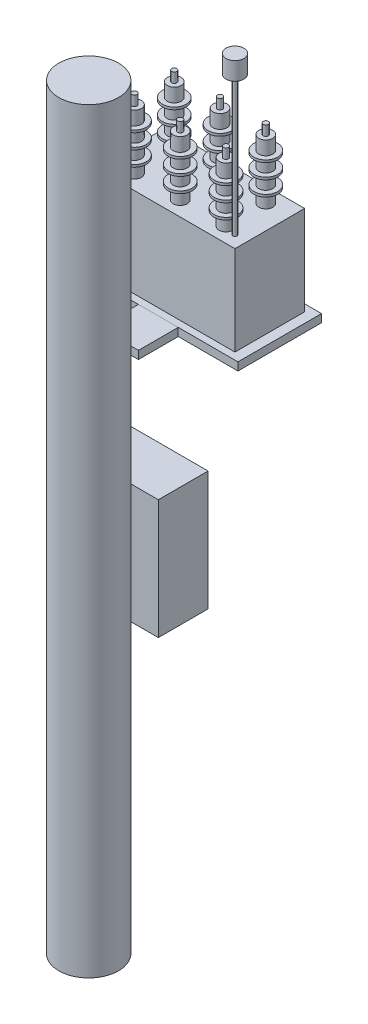
SolidWorks part; units mm, degrees
ref_plane "Front Plane" through (0, 0, 0) normal (0, 0, 1) x (1, 0, 0)
ref_plane "Top Plane" through (0, 0, 0) normal (0, 1, 0) x (1, 0, 0)
ref_plane "Right Plane" through (0, 0, 0) normal (1, 0, 0) x (0, 0, -1)
sketch "Sketch1" plane through (0, 0, 0) normal (0, 1, 0) x (1, 0, 0)
  line L1 (-350, -175) -> (350, -175)
  line L2 (-350, -175) -> (-350, 175)
  line L3 (-350, 175) -> (350, 175)
  line L4 (350, -175) -> (350, 175)
  line L5 (-350, -175) -> (350, 175) construction
  line L6 (-350, 175) -> (350, -175) construction
  point P0 (0, 0)
extrude "Tank" add sketch "Sketch1" along normal blind 450 separate body
sketch "Sketch2" plane through (0, 0, 0) normal (0, 1, 0) x (1, 0, 0)
  line L1 (-400, -210) -> (400, -210)
  line L2 (-400, -210) -> (-400, 210)
  line L3 (-400, 210) -> (400, 210)
  line L4 (400, -210) -> (400, 210)
  line L5 (-400, -210) -> (400, 210) construction
  line L6 (-400, 210) -> (400, -210) construction
  point P0 (0, 0)
extrude "Frame" add sketch "Sketch2" along normal blind 40 from offset 40 separate body
sketch "Sketch3" plane through (0, 0, 0) normal (0, 1, 0) x (1, 0, 0)
  line L0 (-400, -210) -> (400, -210) construction
  line L1 (-100, -410) -> (100, -410)
  line L2 (-100, -410) -> (-100, -210)
  line L3 (-100, -210) -> (100, -210)
  line L4 (100, -410) -> (100, -210)
  line L5 (-100, -410) -> (100, -210) construction
  line L6 (-100, -210) -> (100, -410) construction
  point P0 (0, -310)
extrude "Frame arm" add sketch "Sketch3" along normal blind 40 from offset 40 separate body
sketch "Sketch4" plane through (0, 0, 0) normal (0, 1, 0) x (1, 0, 0)
  line L1 (-200, -410) -> (200, -410)
  line L2 (-200, -410) -> (-200, -160)
  line L3 (-200, -160) -> (200, -160)
  line L4 (200, -410) -> (200, -160)
  line L5 (-200, -410) -> (200, -160) construction
  line L6 (-200, -160) -> (200, -410) construction
  point P0 (0, -285)
extrude "Control cabinet" add sketch "Sketch4" along normal blind 600 from offset 1200 separate body
sketch "Sketch5" plane through (0, 0, 0) normal (0, 1, 0) x (1, 0, 0)
  circle A0 centre (0, -560) radius 150
extrude "Pole" add sketch "Sketch5" along normal blind 3800 from offset 2600 separate body
sketch "Sketch6" plane through (0, 0, 0) normal (0, 1, 0) x (1, 0, 0)
  circle A0 centre (-230, 100) radius 35
extrude "Bushing Source A" add sketch "Sketch6" along normal blind 300 from offset 450 separate body
sketch "Sketch7" plane through (0, 0, 0) normal (0, 1, 0) x (1, 0, 0)
  circle A0 centre (-230, 100) radius 60
extrude "Shed Source A 1" add sketch "Sketch7" along normal blind 12 from offset 519 separate body
sketch "Sketch8" plane through (0, 0, 0) normal (0, 1, 0) x (1, 0, 0)
  circle A0 centre (-230, 100) radius 60
extrude "Shed Source A 2" add sketch "Sketch8" along normal blind 12 from offset 594 separate body
sketch "Sketch9" plane through (0, 0, 0) normal (0, 1, 0) x (1, 0, 0)
  circle A0 centre (-230, 100) radius 60
extrude "Shed Source A 3" add sketch "Sketch9" along normal blind 12 from offset 669 separate body
sketch "Sketch10" plane through (0, 0, 0) normal (0, 1, 0) x (1, 0, 0)
  circle A0 centre (-230, 100) radius 13
extrude "Terminal Source A" add sketch "Sketch10" along normal blind 50 from offset 750 separate body
sketch "Sketch11" plane through (0, 0, 0) normal (0, 1, 0) x (1, 0, 0)
  circle A0 centre (0, 100) radius 35
extrude "Bushing Source B" add sketch "Sketch11" along normal blind 300 from offset 450 separate body
sketch "Sketch12" plane through (0, 0, 0) normal (0, 1, 0) x (1, 0, 0)
  circle A0 centre (0, 100) radius 60
extrude "Shed Source B 1" add sketch "Sketch12" along normal blind 12 from offset 519 separate body
sketch "Sketch13" plane through (0, 0, 0) normal (0, 1, 0) x (1, 0, 0)
  circle A0 centre (0, 100) radius 60
extrude "Shed Source B 2" add sketch "Sketch13" along normal blind 12 from offset 594 separate body
sketch "Sketch14" plane through (0, 0, 0) normal (0, 1, 0) x (1, 0, 0)
  circle A0 centre (0, 100) radius 60
extrude "Shed Source B 3" add sketch "Sketch14" along normal blind 12 from offset 669 separate body
sketch "Sketch15" plane through (0, 0, 0) normal (0, 1, 0) x (1, 0, 0)
  circle A0 centre (0, 100) radius 13
extrude "Terminal Source B" add sketch "Sketch15" along normal blind 50 from offset 750 separate body
sketch "Sketch16" plane through (0, 0, 0) normal (0, 1, 0) x (1, 0, 0)
  circle A0 centre (230, 100) radius 35
extrude "Bushing Source C" add sketch "Sketch16" along normal blind 300 from offset 450 separate body
sketch "Sketch17" plane through (0, 0, 0) normal (0, 1, 0) x (1, 0, 0)
  circle A0 centre (230, 100) radius 60
extrude "Shed Source C 1" add sketch "Sketch17" along normal blind 12 from offset 519 separate body
sketch "Sketch18" plane through (0, 0, 0) normal (0, 1, 0) x (1, 0, 0)
  circle A0 centre (230, 100) radius 60
extrude "Shed Source C 2" add sketch "Sketch18" along normal blind 12 from offset 594 separate body
sketch "Sketch19" plane through (0, 0, 0) normal (0, 1, 0) x (1, 0, 0)
  circle A0 centre (230, 100) radius 60
extrude "Shed Source C 3" add sketch "Sketch19" along normal blind 12 from offset 669 separate body
sketch "Sketch20" plane through (0, 0, 0) normal (0, 1, 0) x (1, 0, 0)
  circle A0 centre (230, 100) radius 13
extrude "Terminal Source C" add sketch "Sketch20" along normal blind 50 from offset 750 separate body
sketch "Sketch21" plane through (0, 0, 0) normal (0, 1, 0) x (1, 0, 0)
  circle A0 centre (-230, -100) radius 35
extrude "Bushing Load A" add sketch "Sketch21" along normal blind 300 from offset 450 separate body
sketch "Sketch22" plane through (0, 0, 0) normal (0, 1, 0) x (1, 0, 0)
  circle A0 centre (-230, -100) radius 60
extrude "Shed Load A 1" add sketch "Sketch22" along normal blind 12 from offset 519 separate body
sketch "Sketch23" plane through (0, 0, 0) normal (0, 1, 0) x (1, 0, 0)
  circle A0 centre (-230, -100) radius 60
extrude "Shed Load A 2" add sketch "Sketch23" along normal blind 12 from offset 594 separate body
sketch "Sketch24" plane through (0, 0, 0) normal (0, 1, 0) x (1, 0, 0)
  circle A0 centre (-230, -100) radius 60
extrude "Shed Load A 3" add sketch "Sketch24" along normal blind 12 from offset 669 separate body
sketch "Sketch25" plane through (0, 0, 0) normal (0, 1, 0) x (1, 0, 0)
  circle A0 centre (-230, -100) radius 13
extrude "Terminal Load A" add sketch "Sketch25" along normal blind 50 from offset 750 separate body
sketch "Sketch26" plane through (0, 0, 0) normal (0, 1, 0) x (1, 0, 0)
  circle A0 centre (0, -100) radius 35
extrude "Bushing Load B" add sketch "Sketch26" along normal blind 300 from offset 450 separate body
sketch "Sketch27" plane through (0, 0, 0) normal (0, 1, 0) x (1, 0, 0)
  circle A0 centre (0, -100) radius 60
extrude "Shed Load B 1" add sketch "Sketch27" along normal blind 12 from offset 519 separate body
sketch "Sketch28" plane through (0, 0, 0) normal (0, 1, 0) x (1, 0, 0)
  circle A0 centre (0, -100) radius 60
extrude "Shed Load B 2" add sketch "Sketch28" along normal blind 12 from offset 594 separate body
sketch "Sketch29" plane through (0, 0, 0) normal (0, 1, 0) x (1, 0, 0)
  circle A0 centre (0, -100) radius 60
extrude "Shed Load B 3" add sketch "Sketch29" along normal blind 12 from offset 669 separate body
sketch "Sketch30" plane through (0, 0, 0) normal (0, 1, 0) x (1, 0, 0)
  circle A0 centre (0, -100) radius 13
extrude "Terminal Load B" add sketch "Sketch30" along normal blind 50 from offset 750 separate body
sketch "Sketch31" plane through (0, 0, 0) normal (0, 1, 0) x (1, 0, 0)
  circle A0 centre (230, -100) radius 35
extrude "Bushing Load C" add sketch "Sketch31" along normal blind 300 from offset 450 separate body
sketch "Sketch32" plane through (0, 0, 0) normal (0, 1, 0) x (1, 0, 0)
  circle A0 centre (230, -100) radius 60
extrude "Shed Load C 1" add sketch "Sketch32" along normal blind 12 from offset 519 separate body
sketch "Sketch33" plane through (0, 0, 0) normal (0, 1, 0) x (1, 0, 0)
  circle A0 centre (230, -100) radius 60
extrude "Shed Load C 2" add sketch "Sketch33" along normal blind 12 from offset 594 separate body
sketch "Sketch34" plane through (0, 0, 0) normal (0, 1, 0) x (1, 0, 0)
  circle A0 centre (230, -100) radius 60
extrude "Shed Load C 3" add sketch "Sketch34" along normal blind 12 from offset 669 separate body
sketch "Sketch35" plane through (0, 0, 0) normal (0, 1, 0) x (1, 0, 0)
  circle A0 centre (230, -100) radius 13
extrude "Terminal Load C" add sketch "Sketch35" along normal blind 50 from offset 750 separate body
sketch "Sketch36" plane through (0, 0, 0) normal (0, 1, 0) x (1, 0, 0)
  circle A0 centre (290, -115) radius 10
extrude "Antenna mast" add sketch "Sketch36" along normal blind 700 from offset 450 separate body
sketch "Sketch37" plane through (0, 0, 0) normal (0, 1, 0) x (1, 0, 0)
  circle A0 centre (290, -115) radius 45
extrude "Antenna radome" add sketch "Sketch37" along normal blind 90 from offset 1150 separate body
